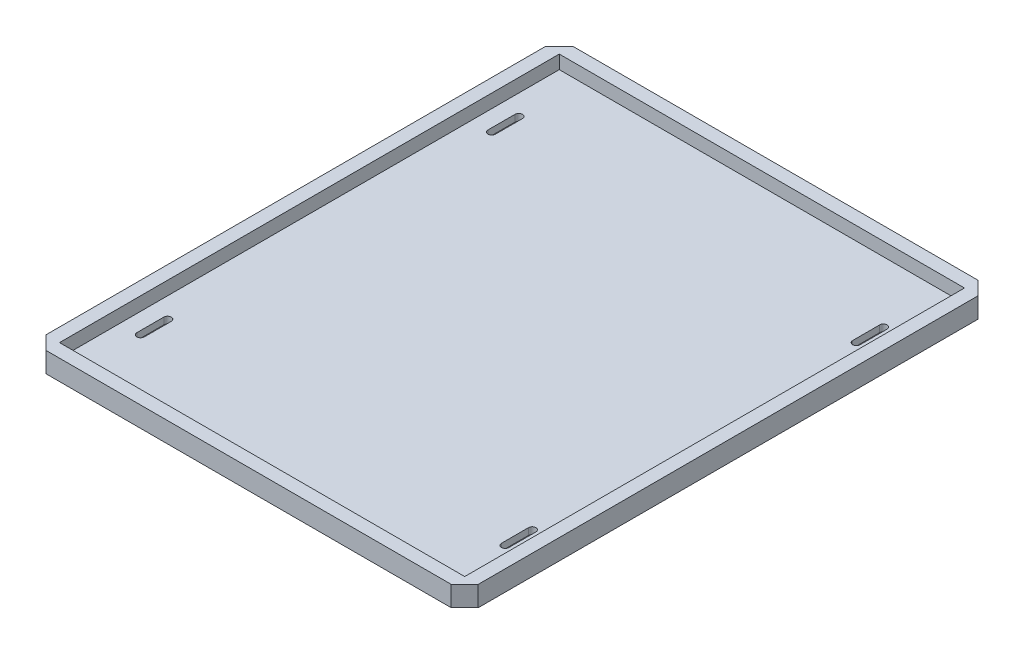
SolidWorks part; units mm, degrees
ref_plane "前视基准面" through (0, 0, 0) normal (0, 0, 1) x (1, 0, 0)
ref_plane "上视基准面" through (0, 0, 0) normal (0, 1, 0) x (1, 0, 0)
ref_plane "右视基准面" through (0, 0, 0) normal (1, 0, 0) x (0, 0, -1)
other "Configuration Table"
sketch "草图1" plane through (0, 0, 0) normal (0, 1, 0) x (1, 0, 0)
  line L1 (-160, 195) -> (160, 195)
  line L2 (-160, 195) -> (-160, -195)
  line L3 (-160, -195) -> (160, -195)
  line L4 (160, 195) -> (160, -195)
  line L5 (-160, 195) -> (160, -195) construction
  line L6 (-160, -195) -> (160, 195) construction
  point P0 (0, 0)
  dimension "D1" = 320
  dimension "D2" = 390
extrude "凸台-拉伸1" add sketch "草图1" along normal blind 5 contours L2 L3 L4 L1
sketch "草图2" plane through (0, 5, 0) normal (0, 1, 0) x (1, 0, 0)
  line L0 (-135, 140) -> (-135, 120) construction
  line L1 (-132.25, 140) -> (-132.25, 120)
  line L2 (-137.75, 140) -> (-137.75, 120)
  line L3 (-68.4518, 0) -> (68.4518, 0) construction
  line L4 (-135, -140) -> (-135, -120) construction
  line L5 (-132.25, -140) -> (-132.25, -120)
  line L6 (0, 30.3993) -> (0, 0) construction
  line L7 (-137.75, -140) -> (-137.75, -120)
  line L8 (135, 140) -> (135, 120) construction
  line L9 (132.25, 140) -> (132.25, 120)
  line L10 (137.75, 140) -> (137.75, 120)
  line L11 (135, -140) -> (135, -120) construction
  line L12 (132.25, -140) -> (132.25, -120)
  line L13 (137.75, -140) -> (137.75, -120)
  arc A0 (-132.25, 140) -> (-137.75, 140) centre (-135, 140) ccw
  arc A1 (-137.75, 120) -> (-132.25, 120) centre (-135, 120) ccw
  arc A2 (-132.25, -140) -> (-137.75, -140) centre (-135, -140) cw
  arc A3 (-137.75, -120) -> (-132.25, -120) centre (-135, -120) cw
  arc A4 (132.25, 140) -> (137.75, 140) centre (135, 140) cw
  arc A5 (137.75, 120) -> (132.25, 120) centre (135, 120) cw
  arc A6 (132.25, -140) -> (137.75, -140) centre (135, -140) ccw
  arc A7 (137.75, -120) -> (132.25, -120) centre (135, -120) ccw
  point P2 (-135, 130)
  point P7 (0, 15.1996)
  point P11 (0, 0)
  point P17 (-135, -130)
  point P24 (135, 130)
  point P31 (135, -130)
  dimension "D1" = 5.5
  dimension "D2" = 20
  dimension "D3" = 130
  dimension "D4" = 135
extrude "切除-拉伸1" cut sketch "草图2" against normal blind 5 contours L1 A1 L2 A0 | L10 A5 L9 A4 | L13 A7 L12 A6 | L5 A3 L7 A2
sketch "草图3" plane through (0, 0, 0) normal (0, 1, 0) x (1, 0, 0)
  line L0 (160, 195) -> (160, -195) construction
  line L1 (-150, 185) -> (150, 185)
  line L2 (-150, 185) -> (-150, -185)
  line L3 (-150, -185) -> (150, -185)
  line L4 (150, 185) -> (150, -185)
  line L5 (-150, 185) -> (150, -185) construction
  line L6 (-150, -185) -> (150, 185) construction
  line L9 (-160, 195) -> (160, 195)
  line L10 (-160, 195) -> (-160, -195)
  line L11 (-160, -195) -> (160, -195)
  line L12 (160, 195) -> (160, -195)
  line L13 (-160, 195) -> (160, -195) construction
  line L14 (-160, -195) -> (160, 195) construction
  point P0 (0, 0)
  point P11 (0, 0)
  dimension "D1" = 10
  dimension "D2" = 10
extrude "凸台-拉伸2" add sketch "草图3" along normal blind 15
chamfer "倒角1" distance 10 angle 45 4 edges at (-160, 7.5, -195) (160, 7.5, -195) (160, 7.5, 195) (-160, 7.5, 195)
